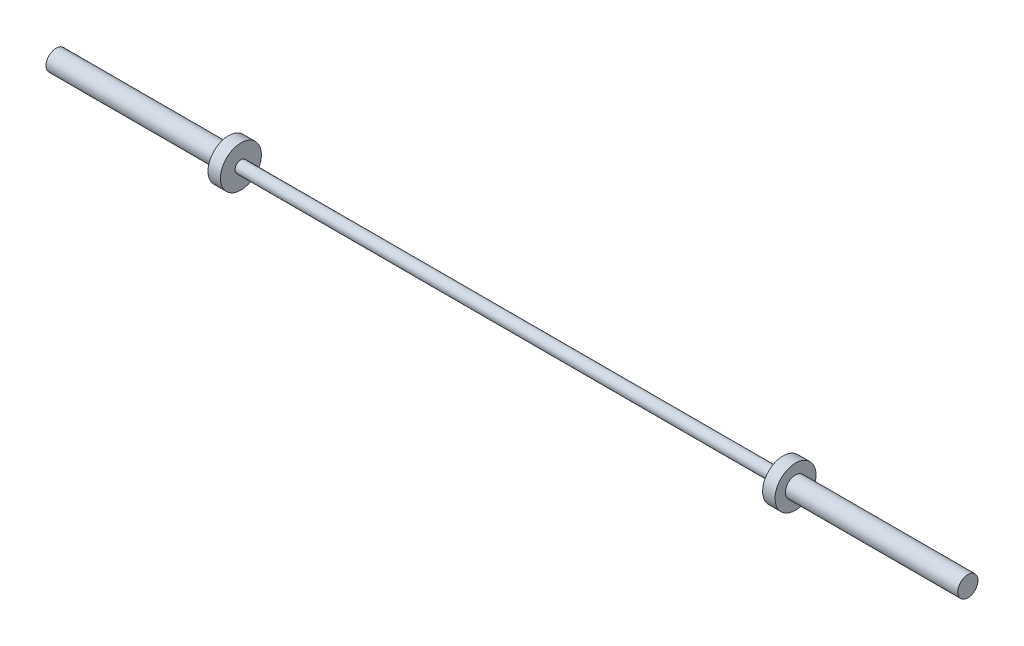
SolidWorks part; units mm, degrees
ref_plane "Front Plane" through (0, 0, 0) normal (0, 0, 1) x (1, 0, 0)
ref_plane "Top Plane" through (0, 0, 0) normal (0, 1, 0) x (1, 0, 0)
ref_plane "Right Plane" through (0, 0, 0) normal (1, 0, 0) x (0, 0, -1)
sketch "Sketch1" plane through (0, 0, 0) normal (0, 0, 1) x (1, 0, 0)
  line L1 (1101.725, 32.4161) -> (1101.725, 56.9161)
  line L2 (1101.725, 56.9161) -> (685.165, 56.9161)
  line L3 (685.165, 56.9161) -> (685.165, 81.9161)
  line L4 (685.165, 81.9161) -> (655.165, 81.9161)
  line L5 (655.165, 81.9161) -> (655.165, 46.6661)
  line L6 (655.165, 46.6661) -> (-655.165, 46.6661)
  line L8 (-1101.725, 32.4161) -> (1101.725, 32.4161)
  line L9 (-655.165, 81.9161) -> (-655.165, 46.6661)
  line L10 (-685.165, 81.9161) -> (-655.165, 81.9161)
  line L11 (-685.165, 56.9161) -> (-685.165, 81.9161)
  line L12 (-1101.725, 56.9161) -> (-685.165, 56.9161)
  line L13 (-1101.725, 32.4161) -> (-1101.725, 56.9161)
  dimension "D2" = 416.56
  dimension "D4" = 24.5
  dimension "D5" = 25
  dimension "D6" = 30
revolve "Revolve1" add sketch "Sketch1" angle 360 about L8
